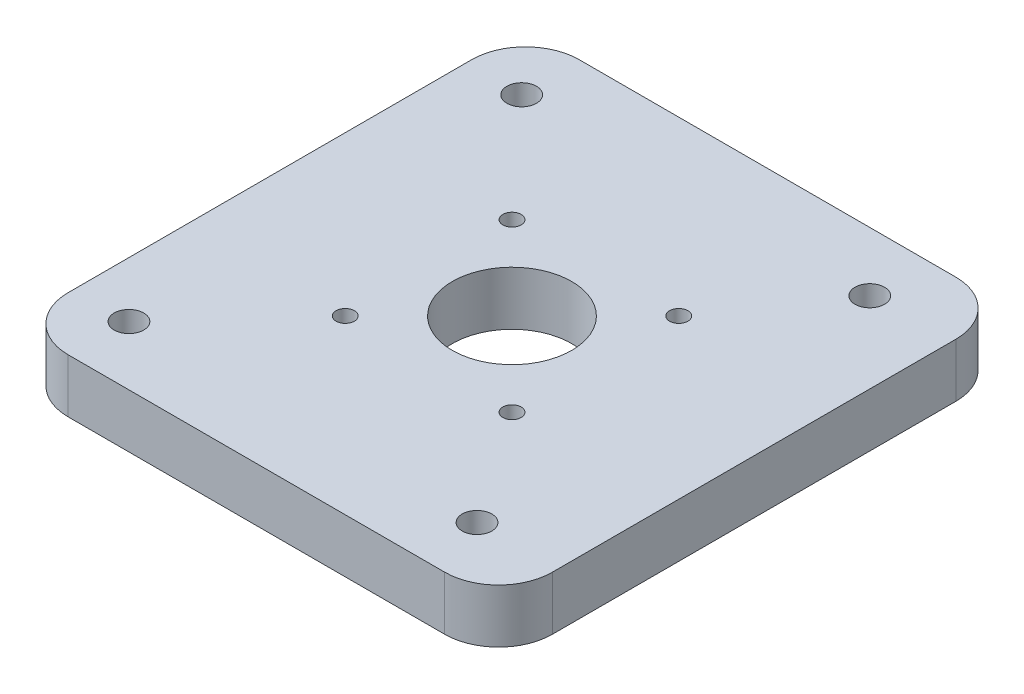
SolidWorks part; units mm, degrees
ref_plane "Front Plane" through (0, 0, 0) normal (0, 0, 1) x (1, 0, 0)
ref_plane "Top Plane" through (0, 0, 0) normal (0, 1, 0) x (1, 0, 0)
ref_plane "Right Plane" through (0, 0, 0) normal (1, 0, 0) x (0, 0, -1)
sketch "Sketch1" plane through (0, 0, 0) normal (0, 1, 0) x (1, 0, 0)
  line L15 (141.6682, -63.6732) -> (-31.3318, -63.6732) construction
  line L16 (-33.8925, 14.3268) -> (-2.8925, 14.3268) construction
  line L19 (-33.8925, 14.3268) -> (-33.8925, -16.6732) construction
  line L20 (-18.3925, 46.3268) -> (-18.3925, -48.6732) construction
  line L21 (141.6682, 61.3268) -> (-31.3318, 61.3268) construction
  line L36 (-53.3925, 46.3268) -> (16.6075, 46.3268)
  line L37 (-63.3925, 36.3268) -> (-63.3925, -38.6732)
  line L38 (-53.3925, -48.6732) -> (16.6075, -48.6732)
  line L40 (-33.8925, -16.6732) -> (-2.8925, -16.6732) construction
  line L41 (-2.8925, 14.3268) -> (-2.8925, -16.6732) construction
  line L42 (141.6682, -63.6732) -> (-60.401, -63.6732)
  line L43 (141.6682, 61.3268) -> (-49.2686, 61.3268)
  line L44 (26.6075, 36.3268) -> (26.6075, -38.6732)
  line L45 (-53.3925, 61.3268) -> (-53.3925, -63.6732) construction
  line L46 (-53.3925, -1.1732) -> (-63.3925, -1.1732) construction
  arc A12 (-63.3925, -38.6732) -> (-53.3925, -48.6732) centre (-53.3925, -38.6732) ccw
  circle A14 centre (-18.3925, -1.1732) radius 11.1
  arc A16 (16.6075, -48.6732) -> (26.6075, -38.6732) centre (16.6075, -38.6732) ccw
  arc A17 (26.6075, 36.3268) -> (16.6075, 46.3268) centre (16.6075, 36.3268) ccw
  arc A18 (-53.3925, 46.3268) -> (-63.3925, 36.3268) centre (-53.3925, 36.3268) ccw
  circle A19 centre (-33.8925, 14.3268) radius 1.5
  circle A28 centre (-2.8925, 14.3268) radius 1.5
  circle A29 centre (-2.8925, -16.6732) radius 1.5
  circle A30 centre (-33.8925, -16.6732) radius 1.5
  point P5 (-63.3925, -48.6732)
  point P15 (11.9089, 43.3268)
  point P29 (-63.3925, 46.3268)
  dimension "D1" = 10
  dimension "D2" = 22.2
  dimension "D8" = 3
  dimension "D9" = 125.4947
  dimension "D5" = 15.5
  dimension "D6" = 15.5
  dimension "D3" = 95
  dimension "D4" = 45
  dimension "D7" = 31
extrude "Boss-Extrude1" add sketch "Sketch1" along normal blind 10
sketch "Sketch2" plane through (0, 0, 0) normal (0, -1, 0) x (1, 0, 0)
  line L0 (11.6075, -35.3268) -> (11.6075, 37.6732) construction
  line L6 (26.6075, -36.3268) -> (26.6075, 38.6732) construction
  line L16 (-53.0911, -35.3268) -> (-53.0911, 37.6732) construction
  line L17 (-53.2689, -38.5768) -> (16.7311, -38.5768) construction
  line L20 (-53.2689, -32.0768) -> (16.7311, -32.0768) construction
  line L22 (-53.3925, -46.3268) -> (16.6075, -46.3268) construction
  line L23 (-53.3925, 48.6732) -> (16.6075, 48.6732) construction
  line L24 (-63.3925, -36.3268) -> (-63.3925, 38.6732) construction
  line L27 (141.6682, 63.6732) -> (-31.3318, 63.6732) construction
  line L28 (141.6682, -61.3268) -> (-31.3318, -61.3268) construction
  line L34 (26.6075, -37.3768) -> (26.6075, 40.9232) construction
  line L35 (141.6682, 63.6732) -> (-31.3318, 63.6732) construction
  line L36 (141.6682, -61.3268) -> (-31.3318, -61.3268) construction
  line L38 (-53.2689, 40.9232) -> (16.7311, 40.9232) construction
  line L39 (-53.2689, 34.4232) -> (16.7311, 34.4232) construction
  circle A24 centre (-53.0911, 37.6732) radius 3.2549
  circle A25 centre (11.6075, 37.6732) radius 3.2549
  circle A26 centre (-53.0911, -35.3268) radius 3.2549
  circle A27 centre (11.6075, -35.3268) radius 3.2549
  dimension "D1" = 15
  dimension "D2" = 11
  dimension "D3" = 11
  dimension "D4" = 73
  dimension "D5" = 73
  dimension "D6" = 11
  dimension "D7" = 10.3014
hole_wizard "CBORE for M3 SHCS2" positions "Sketch10" profile "Sketch11" counterbore size "M3" standard "ANSI Metric" end condition through all
sketch "Sketch10" plane through (0, 0, 0) normal (0, -1, 0) x (-1, 0, 0)
  point P0 (33.8925, 14.3268)
  point P3 (33.8925, -16.6732)
  point P6 (2.8925, -16.6732)
  point P9 (2.8925, 14.3268)
sketch "Sketch11" plane through (-33.8925, 0, -14.3268) normal (1, 0, 0) x (0, 0, -1)
  line L0 (0, 0) -> (0, 10)
  line L1 (0, 10) -> (1.7, 10)
  line L3 (1.7, 10) -> (1.7, 3)
  line L4 (1.7, 3) -> (3.25, 3)
  line L5 (3.25, 3) -> (3.25, 0)
  line L7 (3.25, 0) -> (0, 0)
  line L11 (0, -6.35) -> (0, 107.95) construction
  dimension "Thru Hole Dia." = 3.4
  dimension "Thru Hole Depth" = 10
  dimension "C'Bore Dia." = 6.5
  dimension "C'Bore Depth" = 3
sketch "Sketch14" plane through (0, 0, 0) normal (0, -1, 0) x (1, 0, 0)
  line L0 (-63.3925, -18.8268) -> (-63.3925, 21.1732)
  line L1 (-63.3925, -36.3268) -> (-63.3925, 38.6732) construction
  line L2 (-63.3925, 1.1732) -> (-63.3925, 21.1732)
  line L6 (-45.2435, 8.8636) -> (-45.2435, -6.5172)
  line L9 (-63.3925, 21.1732) -> (-63.3925, 1.1732)
  line L10 (-45.2435, 1.1732) -> (-63.3925, 1.1732) construction
  arc A0 (-48.9438, 17.9948) -> (-48.1943, 15.8776) centre (-48.0515, 17.1194) ccw
  arc A1 (-49.1181, 18.4198) -> (-49.2529, 18.4223) centre (-48.4206, 60.414) cw
  arc A2 (-45.2435, 8.8636) -> (-48.0429, 15.8027) centre (-55.2435, 8.8636) ccw
  arc A3 (-51.9709, 18.3589) -> (-49.5026, 18.2232) centre (-50.7265, 18.4774) ccw
  arc A4 (-54.9638, 18.7196) -> (-52.5116, 18.408) centre (-53.7142, 18.7489) ccw
  arc A5 (-57.7484, 19.119) -> (-55.4694, 18.6696) centre (-56.6983, 18.4409) ccw
  arc A6 (-60.5441, 20.2018) -> (-58.1972, 19.3572) centre (-59.3421, 19.8589) ccw
  arc A7 (-60.5441, 20.2018) -> (-63.3925, 21.1732) centre (-48.4206, 60.414) cw
  arc A8 (-57.902, 19.4982) -> (-57.9117, 19.5005) centre (-48.4206, 60.414) cw
  arc A9 (-55.1736, 18.9605) -> (-55.1834, 18.9621) centre (-48.4206, 60.414) cw
  arc A10 (-52.1973, 18.5842) -> (-52.2483, 18.5888) centre (-48.4206, 60.414) cw
  arc A11 (-48.0429, 15.8027) -> (-48.1943, 15.8776) centre (-48.2229, 15.6292) ccw
  arc A12 (-49.1181, 18.4198) -> (-48.9438, 17.9948) centre (-49.1222, 18.1698) cw
  arc A13 (-49.2529, 18.4223) -> (-49.5026, 18.2232) centre (-49.2578, 18.1723) ccw
  arc A14 (-52.1973, 18.5842) -> (-51.9709, 18.3589) centre (-52.2197, 18.3352) cw
  arc A15 (-52.2483, 18.5888) -> (-52.5116, 18.408) centre (-52.2711, 18.3398) ccw
  arc A16 (-55.1736, 18.9605) -> (-54.9638, 18.7196) centre (-55.2138, 18.7137) cw
  arc A17 (-55.4694, 18.6696) -> (-55.1834, 18.9621) centre (-55.2236, 18.7153) cw
  arc A18 (-57.902, 19.4982) -> (-57.7484, 19.119) centre (-57.9584, 19.2547) cw
  arc A19 (-58.1972, 19.3572) -> (-57.9117, 19.5005) centre (-57.9682, 19.2569) cw
  arc A20 (-55.1736, -16.6141) -> (-54.9638, -16.3732) centre (-55.2138, -16.3674) ccw
  arc A21 (-55.4694, -16.3232) -> (-55.1834, -16.6157) centre (-55.2236, -16.369) ccw
  arc A22 (-57.7484, -16.7727) -> (-55.4694, -16.3232) centre (-56.6983, -16.0946) cw
  arc A23 (-57.902, -17.1519) -> (-57.7484, -16.7727) centre (-57.9584, -16.9083) ccw
  arc A24 (-58.1972, -17.0109) -> (-57.9117, -17.1541) centre (-57.9682, -16.9106) ccw
  arc A25 (-60.5441, -17.8555) -> (-58.1972, -17.0109) centre (-59.3421, -17.5125) cw
  arc A26 (-60.5441, -17.8555) -> (-63.3925, -18.8268) centre (-48.4206, -58.0677) ccw
  arc A27 (-54.9638, -16.3732) -> (-52.5116, -16.0617) centre (-53.7142, -16.4026) cw
  arc A28 (-52.2483, -16.2424) -> (-52.5116, -16.0617) centre (-52.2711, -15.9935) cw
  arc A29 (-52.1973, -16.2378) -> (-51.9709, -16.0125) centre (-52.2197, -15.9888) ccw
  arc A30 (-51.9709, -16.0125) -> (-49.5026, -15.8768) centre (-50.7265, -16.131) cw
  arc A31 (-49.2529, -16.0759) -> (-49.5026, -15.8768) centre (-49.2578, -15.826) cw
  arc A32 (-49.1181, -16.0734) -> (-48.9438, -15.6484) centre (-49.1222, -15.8235) ccw
  arc A33 (-48.9438, -15.6484) -> (-48.1943, -13.5312) centre (-48.0515, -14.773) cw
  arc A34 (-48.0429, -13.4563) -> (-48.1943, -13.5312) centre (-48.2229, -13.2828) cw
  arc A35 (-45.2435, -6.5172) -> (-48.0429, -13.4563) centre (-55.2435, -6.5172) cw
  arc A36 (-57.902, -17.1519) -> (-57.9117, -17.1541) centre (-48.4206, -58.0677) ccw
  arc A37 (-55.1736, -16.6141) -> (-55.1834, -16.6157) centre (-48.4206, -58.0677) ccw
  arc A38 (-52.1973, -16.2378) -> (-52.2483, -16.2424) centre (-48.4206, -58.0677) ccw
  arc A39 (-49.1181, -16.0734) -> (-49.2529, -16.0759) centre (-48.4206, -58.0677) ccw
  point P6 (-55.7968, 4.1732)
  point P32 (-51.9735, 18.5646)
  point P37 (-54.9517, 18.9249)
  point P42 (-57.4932, 19.4056)
  line M27 (-63.3925, 38.6732) -> (-63.3925, -36.3268)
  dimension "D5" = 42
  dimension "D1" = 10
  dimension "D2" = 2.5
  dimension "D4" = 2.5
  dimension "D6" = 2.5
  dimension "D7" = 2.5
  dimension "D8" = 2.5
  dimension "D9" = 3
  dimension "D10" = 3
  dimension "D11" = 3
  dimension "D12" = 3
  dimension "D13" = 0.25
  dimension "D3" = 20
extrude "Boss-Extrude2" add sketch "Sketch14" along normal blind 15 contours L10 L6 A2 A11 A0 A12 A1 A13 A3 A14 A10 A15 A4 A16 A9 A17 A5 A18 A8 A19 A6 A7 M27 | L6 L10 L0 A26 A25 A24 A36 A23 A22 A21 A37 A20 A27 A28 A38 A29 A30 A31 A39 A32 A33 A34 A35
hole_wizard "CBORE for M5 Pan Head Machine Screw1" positions "Sketch17" profile "Sketch18" counterbore size "M5" standard "ANSI Metric" end condition through all
sketch "Sketch17" plane through (0, 0, 0) normal (0, -1, 0) x (-1, 0, 0)
  point P0 (53.0911, 35.3268)
  point P3 (-11.6075, 35.3268)
  point P6 (-11.6075, -37.6732)
  point P9 (53.0911, -37.6732)
sketch "Sketch18" plane through (-53.0911, 0, -35.3268) normal (1, 0, 0) x (0, 0, -1)
  line L0 (0, 0) -> (0, 10)
  line L1 (0, 10) -> (2.75, 10)
  line L3 (2.75, 10) -> (2.75, 3.7)
  line L4 (2.75, 3.7) -> (5.5, 3.7)
  line L5 (5.5, 3.7) -> (5.5, 0)
  line L7 (5.5, 0) -> (0, 0)
  line L11 (0, -6.35) -> (0, 107.95) construction
  dimension "Thru Hole Dia." = 5.5
  dimension "Thru Hole Depth" = 10
  dimension "C'Bore Dia." = 11
  dimension "C'Bore Depth" = 3.7
